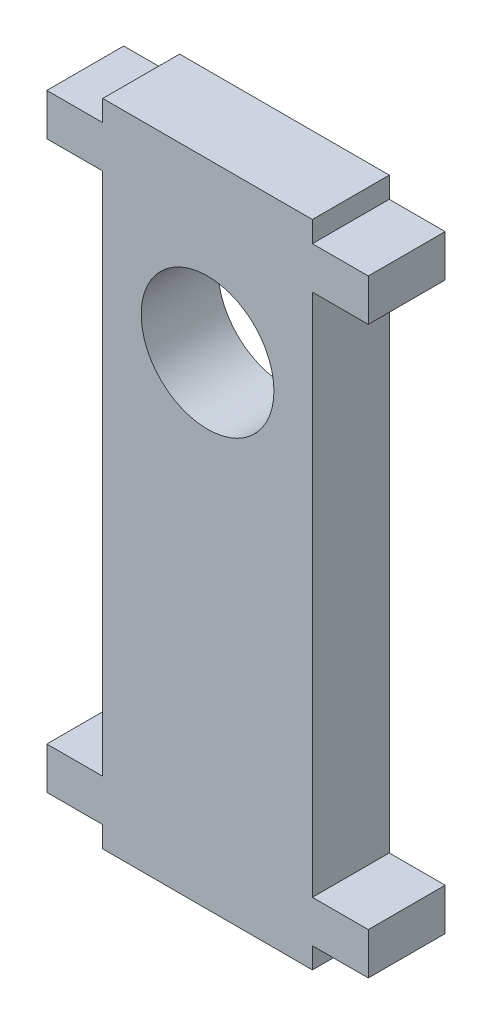
SolidWorks part; units mm, degrees
ref_plane "Plan de face" through (0, 0, 0) normal (0, 0, 1) x (1, 0, 0)
ref_plane "Plan de dessus" through (0, 0, 0) normal (0, 1, 0) x (1, 0, 0)
ref_plane "Plan de droite" through (0, 0, 0) normal (1, 0, 0) x (0, 0, -1)
sketch "Esquisse1" plane through (0, 0, 0) normal (0, 0, 1) x (1, 0, 0)
  line L0 (15, 36.5) -> (15, 0) construction
  line L1 (0, 0) -> (30, 0) construction
  line L2 (0, 0) -> (0, 40) construction
  line L3 (0, 81) -> (0, 6)
  line L4 (30, 0) -> (30, 40) construction
  line L5 (30, 81) -> (30, 6)
  line L6 (3, 30) -> (3, 0) construction
  line L7 (27, 30) -> (27, 0) construction
  line L8 (0, 40) -> (0, 6) construction
  line L9 (0, 6) -> (-8, 6)
  line L10 (-8, 6) -> (-8, 0)
  line L11 (-8, 0) -> (0, 0)
  line L12 (0, 0) -> (0, -3)
  line L13 (0, -3) -> (30, -3)
  line L14 (30, -3) -> (30, 0)
  line L15 (30, 0) -> (38, 0)
  line L16 (38, 0) -> (38, 6)
  line L17 (38, 6) -> (30, 6)
  line L18 (30, 6) -> (30, 40) construction
  line L20 (30, 81) -> (38, 81)
  line L21 (38, 81) -> (38, 87)
  line L22 (38, 87) -> (30, 87)
  line L23 (30, 87) -> (30, 90)
  line L24 (5, 90) -> (25, 90)
  line L25 (0, 90) -> (0, 87)
  line L26 (0, 87) -> (-8, 87)
  line L27 (-8, 87) -> (-8, 81)
  line L28 (-8, 81) -> (0, 81)
  line L30 (0, 90) -> (5, 90)
  line L31 (5, 90) -> (5, 100) construction
  line L32 (5, 100) -> (25, 100) construction
  line L33 (25, 100) -> (25, 90) construction
  line L34 (25, 90) -> (30, 90)
  line L35 (15, 93.5) -> (15, -3) construction
  line L44 (-18.4801, 81) -> (50.2693, 81) construction
  circle A0 centre (15, 66) radius 51.5 construction
  circle A5 centre (15, 66) radius 15 construction
  circle A6 centre (15, 66) radius 9.5
  dimension "D23" = 15
  dimension "D3" = 30
  dimension "D4" = 3
  dimension "D9" = 75
  dimension "D10" = 6
  dimension "D11" = 8
  dimension "D12" = 3
  dimension "D13" = 6
  dimension "D17" = 20
  dimension "D18" = 10
  dimension "D22" = 6
extrude "Boss.-Extru.1" add sketch "Esquisse1" along normal blind 11
sketch "Esquisse2" plane through (0, 0, 11) normal (0, 0, 1) x (1, 0, 0)
  circle A0 centre (-8.0125, 12.9998) radius 1.15
  circle A1 centre (38.0125, 12.9998) radius 1.15
  circle A2 centre (31.215, 12.9998) radius 1.15
  circle A3 centre (-1.215, 12.9998) radius 1.15
  dimension "D1" = 2.3
